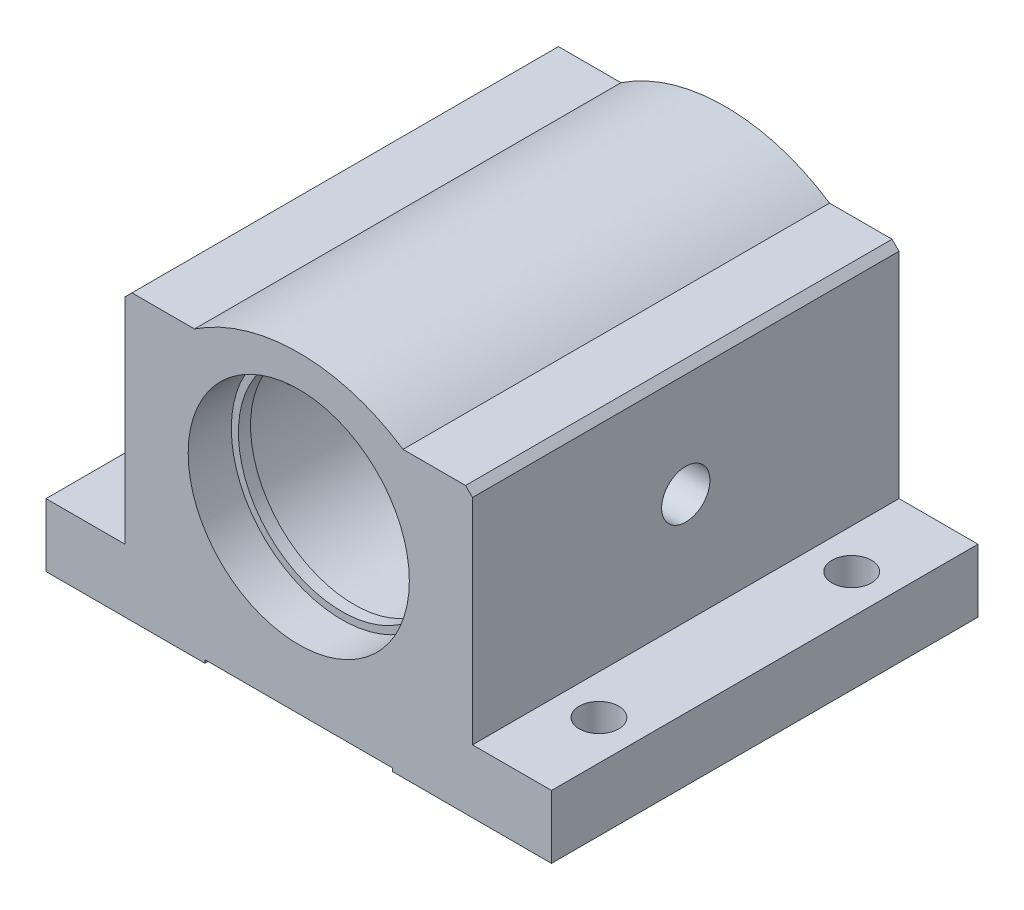
SolidWorks part; units mm, degrees
ref_plane "Front Plane" through (0, 0, 0) normal (0, 0, 1) x (1, 0, 0)
ref_plane "Top Plane" through (0, 0, 0) normal (0, 1, 0) x (1, 0, 0)
ref_plane "Right Plane" through (0, 0, 0) normal (1, 0, 0) x (0, 0, -1)
sketch "Sketch1" plane through (0, 0, 0) normal (0, 0, 1) x (1, 0, 0)
  line L0 (-25.4, -9.525) -> (-17.4625, -9.525)
  line L1 (-25.4, 15.875) -> (25.4, 15.875)
  line L2 (-25.4, 15.875) -> (-25.4, -15.875)
  line L3 (-25.4, -15.875) -> (25.4, -15.875)
  line L4 (25.4, 15.875) -> (25.4, -15.875)
  line L5 (-17.4625, -9.525) -> (-17.4625, 12.7)
  line L6 (-17.4625, 12.7) -> (17.4625, 12.7)
  line L7 (17.4625, 12.7) -> (17.4625, -9.525)
  line L8 (17.4625, -9.525) -> (25.4, -9.525)
  line L9 (0, 1.5748) -> (0, -15.875) construction
  circle A0 centre (0, 1.5748) radius 11.1125
  point P4 (25.4, 0)
  point P5 (0, 15.875)
  dimension "ID | For Bearing OD" = 22.225
  dimension "Overall Height" = 31.75
  dimension "Overall Width" = 50.8
  dimension "Base Thickness" = 6.35
  dimension "K" = 28.575
  dimension "G" = 34.925
  dimension "Center Height" = 17.4498
sketch "Sketch2" plane through (0, 0, 0) normal (1, 0, 0) x (0, 0, -1)
  line L0 (-21.4312, 0) -> (21.4312, 0) construction
  line L2 (0, 15.875) -> (0, -15.875) construction
  line L3 (0, 15.875) -> (0, -15.875) construction
  circle A0 centre (0, 1.5748) radius 2.4257
  point P2 (0, 0)
  point P11 (-15.875, 0)
  dimension "Grease Hole Diameter" = 4.8514
  dimension "Overall Length" = 42.8625
  dimension "For Maximum Bearing Length" = 31.75
sketch "Sketch3" plane through (0, 0, 0) normal (0, 1, 0) x (1, 0, 0)
  line L1 (-25.4, 21.4312) -> (25.4, 21.4313)
  line L2 (-25.4, 21.4312) -> (-25.4, -21.4313)
  line L3 (-25.4, -21.4313) -> (25.4, -21.4313)
  line L4 (25.4, 21.4313) -> (25.4, -21.4313)
  line L5 (-21.4376, 12.7) -> (21.4376, 12.7) construction
  line L6 (-21.4376, 12.7) -> (-21.4376, -12.7) construction
  line L7 (-21.4376, -12.7) -> (21.4376, -12.7) construction
  line L8 (21.4376, 12.7) -> (21.4376, -12.7) construction
  circle A0 centre (-21.4376, 12.7) radius 1.9844
  point P4 (0, 21.4312)
  point P5 (25.4, 0)
  point P12 (0, 12.7)
  point P13 (21.4376, 0)
  dimension "Mounting Hole Diameter" = 3.9688
  dimension "Mounting Hole Center to Center, Length" = 25.4
  dimension "Mounting Hole Center to Center, Width" = 42.8752
sketch "Sketch4" plane through (0, 0, 0) normal (0, 0, 1) x (1, 0, 0)
  line L0 (-25.4, -9.525) -> (-17.4625, -9.525) construction
  line L1 (-25.4, -9.525) -> (-17.4625, -9.525)
  line L2 (-25.4, -15.875) -> (25.4, -15.875) construction
  line L3 (17.4625, -9.525) -> (25.4, -9.525) construction
  line L4 (17.4625, 12.7) -> (17.4625, -9.525) construction
  line L5 (-17.4625, 12.7) -> (17.4625, 12.7) construction
  line L6 (-17.4625, -9.525) -> (-17.4625, 12.7) construction
  line L7 (-25.4, -15.875) -> (-9.4298, -15.875)
  line L8 (17.4625, -9.525) -> (25.4, -9.525)
  line L9 (17.4625, 12.7) -> (17.4625, -9.525)
  line L10 (-17.4625, 12.7) -> (-10.4775, 12.7)
  line L11 (-17.4625, -9.525) -> (-17.4625, 12.7)
  line L12 (-25.4, -9.525) -> (-25.4, -15.875)
  line L13 (25.4, -9.525) -> (25.4, -15.875)
  line L14 (10.4775, 12.7) -> (17.4625, 12.7)
  line L15 (-25.4, 15.875) -> (25.4, 15.875) construction
  line L16 (-9.4298, -15.875) -> (-9.4297, -15.5575)
  line L17 (-9.4297, -15.5575) -> (9.4297, -15.5575)
  line L18 (9.4297, -15.5575) -> (9.4298, -15.875)
  line L19 (0, 1.5748) -> (0, -15.875) construction
  line L22 (9.4298, -15.875) -> (25.4, -15.875)
  circle A0 centre (0, 1.5748) radius 11.1125 construction
  circle A1 centre (0, 1.5748) radius 11.1125
  arc A2 (-10.4775, 12.7) -> (10.4775, 12.7) centre (0, -3.0004) cw
  point P14 (0, 15.875)
  point P17 (0, 15.875)
  point P20 (0, -15.5575)
  dimension "D1" = 20.955
  dimension "D2" = 18.8595
  dimension "D3" = 0.3175
extrude "Boss-Extrude1" add sketch "Sketch4" along normal up to vertex (21.4312 mm away) from vertex at -21.4312 starting at point (0, 0, -21.4312)
sketch "Sketch5" plane through (0, -9.525, 0) normal (0, 1, 0) x (1, 0, 0)
  circle A0 centre (-21.4376, 12.7) radius 1.9844 construction
  circle A1 centre (-21.4376, 12.7) radius 1.9844
  circle A2 centre (21.4376, 12.7) radius 1.9844
  circle A3 centre (21.4376, -12.7) radius 1.9844
  circle A4 centre (-21.4376, -12.7) radius 1.9844
extrude "Cut-Extrude1" cut sketch "Sketch5" against normal through all
chamfer "Chamfer1" distance 0.6985 angle 45 2 edges at (-17.4625, 12.7, 0) (17.4625, 12.7, 0)
ref_plane "Plane1" through (0, 0, 15.875) normal (0, 0, 1) x (1, 0, 0)
sketch "Sketch6" plane through (0, 0, 15.875) normal (0, 0, 1) x (1, 0, 0)
  circle A0 centre (0, 1.5748) radius 11.8237
  dimension "Retaining Ring Slot OD" = 23.6474
extrude "Cut-Extrude2" cut sketch "Sketch6" along normal blind 1.2192
mirror "Mirror1" about plane through (0, 0, 0) normal (0, 0, 1) of "Cut-Extrude2"
sketch "Sketch7" plane through (17.4625, 0, 0) normal (1, 0, 0) x (0, 0, -1)
  circle A0 centre (0, 1.5748) radius 2.4257 construction
  circle A1 centre (0, 1.5748) radius 2.4257
extrude "Cut-Extrude3" cut sketch "Sketch7" against normal up to next
sketch "Sketch8" plane through (0, 0, 15.875) normal (0, 0, 1) x (1, 0, 0)
  line L0 (0, 1.5748) -> (-6.8519, 8.4267) construction
  line L1 (6.8519, 8.4267) -> (8.3606, 9.9354) construction
  line L2 (0, 1.5748) -> (0, 15.875) construction
  line L3 (0, -10.2489) -> (0, -9.5377) construction
  line L4 (0, -9.5377) -> (0, -8.8265) construction
  line L5 (-4.3582, 9.9492) -> (-5.1789, 12.204)
  line L6 (-6.8748, 8.9506) -> (-6.3788, 8.5343)
  line L7 (-5.558, 9.5125) -> (-4.8256, 8.4665) construction
  line L8 (0, -8.8265) -> (0, -8.1153) construction
  line L9 (-4.8256, 8.4665) -> (0, 1.5748) construction
  line L10 (-7.3548, 8.9296) -> (-8.3606, 9.9354) construction
  line L11 (-7.3548, 8.9296) -> (-7.1034, 8.6782) construction
  line L12 (-7.1034, 8.6782) -> (-6.8519, 8.4267) construction
  line L13 (6.8748, 8.9506) -> (6.3788, 8.5343)
  line L14 (4.3582, 9.9492) -> (5.1789, 12.204)
  circle A0 centre (0, 1.5748) radius 11.8237 construction
  arc A1 (-8.3606, 9.9354) -> (8.3606, 9.9354) centre (0, 1.5748) ccw
  arc A2 (-7.3548, 8.9296) -> (7.3548, 8.9296) centre (0, 1.5748) ccw
  circle A3 centre (0, 1.5748) radius 11.1125 construction
  arc A4 (10.4775, 12.7) -> (-10.4775, 12.7) centre (0, -3.0004) ccw construction
  arc A6 (-7.3548, 8.9296) -> (-6.8748, 8.9506) centre (-7.1034, 8.6782) cw
  arc A9 (-8.3606, 9.9354) -> (-5.1789, 12.204) centre (0, 1.5748) cw
  arc A10 (-6.3788, 8.5343) -> (-4.3582, 9.9492) centre (-5.558, 9.5125) ccw
  circle A11 centre (0, 1.5748) radius 9.6901 construction
  circle A12 centre (-5.558, 9.5125) radius 0.6384
  arc A13 (7.3548, 8.9296) -> (6.8748, 8.9506) centre (7.1034, 8.6782) ccw
  circle A14 centre (5.558, 9.5125) radius 0.6384
  arc A15 (6.3788, 8.5343) -> (4.3582, 9.9492) centre (5.558, 9.5125) cw
  arc A16 (8.3606, 9.9354) -> (5.1789, 12.204) centre (0, 1.5748) ccw
  point P20 (-5.1918, 8.9895)
  dimension "D3" = 30
  dimension "D4" = 10
  dimension "D1" = 45
extrude "Boss-Extrude2" add sketch "Sketch8" along normal blind 1.2192 separate body
mirror "Mirror2" about plane through (0, 0, 0) normal (0, 0, 1) of bodies 109
equation "\"D1@Sketch4\"=0.6*\"G@Sketch1\""
equation "\"D2@Sketch4\"=\"D1@Sketch4\"*.9"
equation "\"D1@Chamfer1\"=.02*\"G@Sketch1\""
equation "\"D3@Sketch4\"=.05*\"Base Thickness@Sketch1\""
equation "\"D1@Boss-Extrude2\"=\"Retaining Ring Slot Thickness@Cut-Extrude2\""
